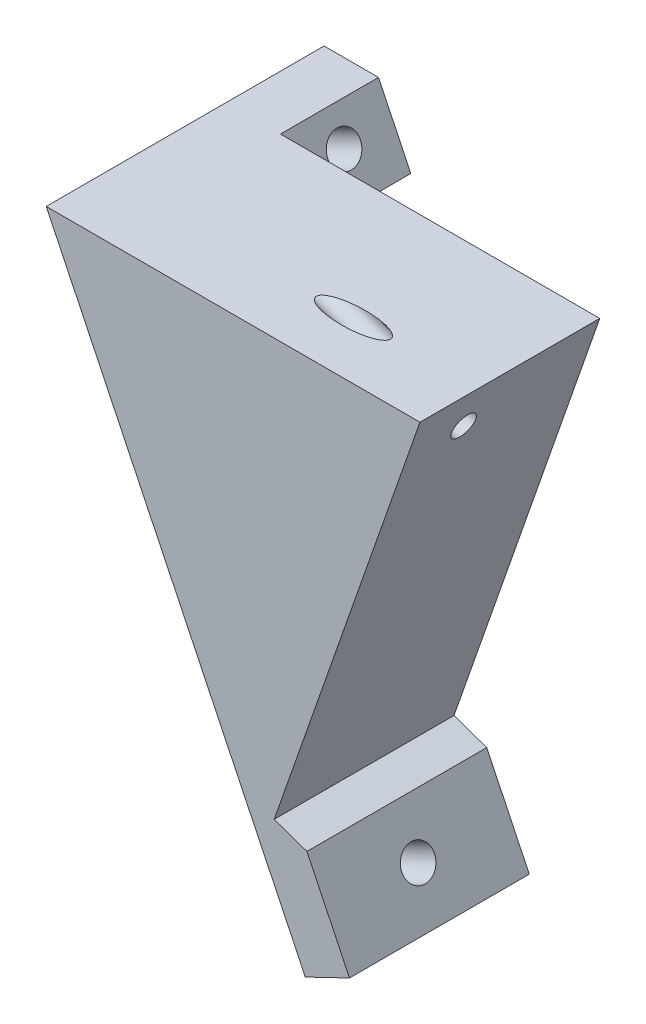
SolidWorks part; units mm, degrees
material "ABS"
ref_plane "Front Plane" through (0, 0, 0) normal (0, 0, 1) x (1, 0, 0)
ref_plane "Top Plane" through (0, 0, 0) normal (0, 1, 0) x (1, 0, 0)
ref_plane "Right Plane" through (0, 0, 0) normal (1, 0, 0) x (0, 0, -1)
sketch "Sketch1" plane through (0, 0, 0) normal (0, 0, 1) x (1, 0, 0)
  line L0 (-36.2386, 24.2413) -> (-9.7428, -30.7587)
  line L1 (-9.7428, -30.7587) -> (9.4941, 24.2413)
  line L2 (9.4941, 24.2413) -> (-36.2386, 24.2413)
  dimension "D1" = 55
  dimension "D2" = 55
  dimension "D3" = 45
extrude "Boss-Extrude1" add sketch "Sketch1" along normal blind 22
sketch "Sketch6" plane through (-19.9343, -9.6032, 0) normal (-0.9009, -0.434, 0) x (0, 0, 1)
  line L0 (22, 37.5671) -> (22, -23.4823) construction
  line L1 (0, 37.5671) -> (-12, 37.5671)
  line L2 (0, 37.5671) -> (0, 25.5671)
  line L3 (0, 25.5671) -> (-12, 25.5671)
  line L4 (-12, 37.5671) -> (-12, 25.5671)
  line L5 (0, -23.4823) -> (22, -23.4823)
  line L6 (0, -23.4823) -> (0, -35.4823)
  line L7 (0, -35.4823) -> (22, -35.4823)
  line L8 (22, -23.4823) -> (22, -35.4823)
  dimension "D1" = 12
  dimension "D2" = 12
  dimension "D3" = 0
  dimension "D4" = 12
extrude "Boss-Extrude4" add sketch "Sketch6" against normal blind 6
sketch "Sketch8" plane through (0, 0, 0) normal (0, 0, -1) x (-1, 0, 0)
  line L0 (9.7428, -30.7587) -> (4.3373, -28.1546)
  line L1 (4.3373, -28.1546) -> (8.3431, -26.7568)
  line L2 (9.7428, -30.7587) -> (-9.4941, 24.2413) construction
  line L3 (8.3431, -26.7568) -> (9.7428, -30.7587)
extrude "Boss-Extrude5" add sketch "Sketch8" against normal up to vertex (22 mm away)
sketch "Sketch9" plane through (-14.5288, -6.9992, 0) normal (0.9009, 0.434, 0) x (0, 0, -1)
  line L2 (12, 25.5671) -> (0, 25.5671) construction
  line L3 (0, -35.4823) -> (-22, -35.4823) construction
  line L4 (-22, -35.4823) -> (-22, -23.4823) construction
  circle A0 centre (6, 30.5671) radius 2
  circle A1 centre (-11, -29.4823) radius 2
  point P9 (6, 25.5671)
  point P12 (-11, -35.4823)
  point P15 (-22, -29.4823)
  dimension "D1" = 4
  dimension "D2" = 4
  dimension "D3" = 5
  dimension "D4" = 0
  dimension "D5" = 0
  dimension "D6" = 0
extrude "Cut-Extrude9" cut sketch "Sketch9" against normal blind 6
sketch "Sketch10" plane through (0.9048, -0.3164, 0) normal (0.9439, -0.3301, 0) x (0, 0, -1)
  line L0 (-22, 26.0166) -> (0, 26.0166) construction
  line L2 (-22, -28.011) -> (-22, 26.0166) construction
  circle A0 centre (-15, 21.0166) radius 1.5
  dimension "D1" = 3
  dimension "D2" = 5
  dimension "D3" = 7
extrude "Cut-Extrude10" cut sketch "Sketch10" against normal blind 36
sketch "Sketch11" plane through (0, 0, 0) normal (0, 0, 1) x (1, 0, 0)
  line L0 (-36.2386, 24.2413) -> (-29.5787, 24.2413)
  line L1 (-29.5787, 24.2413) -> (-30.8332, 26.8454)
  line L2 (-30.8332, 26.8454) -> (-36.2386, 24.2413)
extrude "Cut-Extrude11" cut sketch "Sketch11" against normal blind 36
